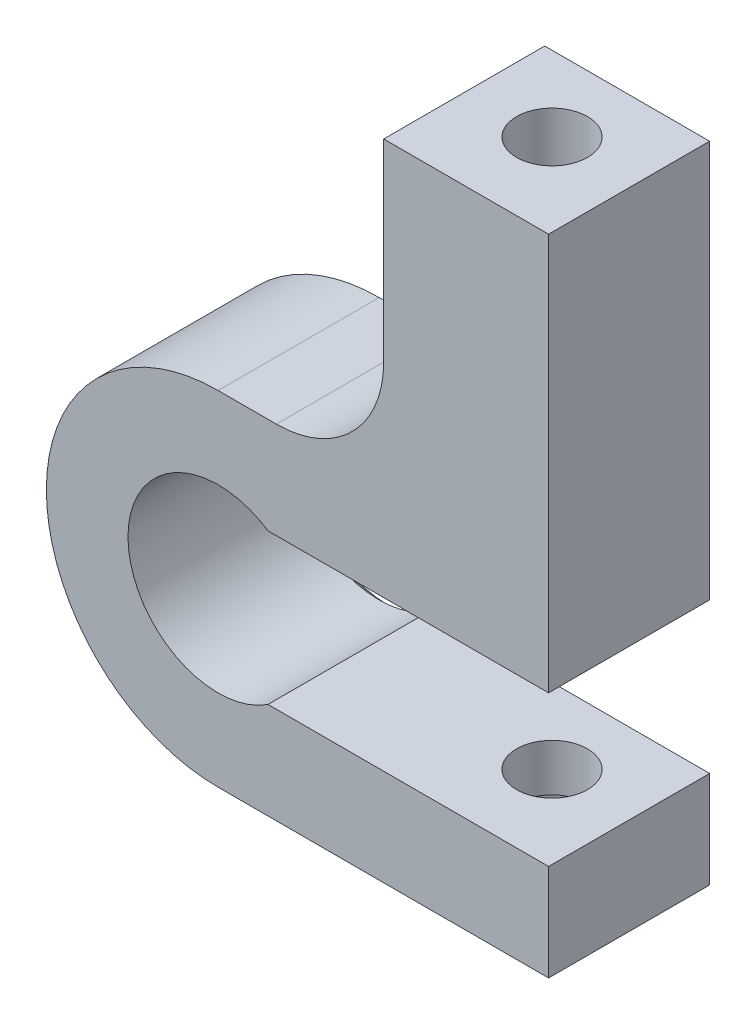
SolidWorks part; units mm, degrees
ref_plane "Front Plane" through (0, 0, 0) normal (0, 0, 1) x (1, 0, 0)
ref_plane "Top Plane" through (0, 0, 0) normal (0, 1, 0) x (1, 0, 0)
ref_plane "Right Plane" through (0, 0, 0) normal (1, 0, 0) x (0, 0, -1)
sketch "Sketch1" plane through (0, 0, 0) normal (0, 0, 1) x (1, 0, 0)
  line L0 (0, 8) -> (15.389, 8)
  line L1 (15.389, 8) -> (15.389, 3.5)
  line L2 (15.389, 3.5) -> (2.3216, 3.5)
  line L3 (-11.5353, 0) -> (18.1518, 0) construction
  line L4 (15.389, -3.5) -> (2.3216, -3.5)
  line L5 (15.389, -8) -> (15.389, -3.5)
  line L6 (0, -8) -> (15.389, -8)
  arc A0 (2.3216, 3.5) -> (2.3216, -3.5) centre (0, 0) ccw
  arc A2 (0, 8) -> (0, -8) centre (0, 0) ccw
  dimension "D1" = 4.2
  dimension "D2" = 8
  dimension "D3" = 15.389
  dimension "D4" = 7
extrude "Boss-Extrude1" add sketch "Sketch1" along normal blind 8
sketch "Sketch2" plane through (0, -8, 0) normal (0, -1, 0) x (1, 0, 0)
  line L1 (0, 8) -> (15.389, 8) construction
  line L3 (0, 8) -> (0, 0) construction
  circle A0 centre (11.549, 4) radius 1.65
  dimension "D1" = 4
  dimension "D2" = 3.3
  dimension "D3" = 11.549
extrude "Cut-Extrude1" cut sketch "Sketch2" against normal through all
sketch "Sketch3" plane through (0, -8, 0) normal (0, -1, 0) x (1, 0, 0)
  circle A0 centre (11.549, 4) radius 3
  dimension "D1" = 6
extrude "Cut-Extrude2" cut sketch "Sketch3" against normal blind 2.3
sketch "Sketch4" plane through (0, 3.5, 0) normal (0, -1, 0) x (1, 0, 0)
  line L0 (15.389, 8) -> (15.389, 0) construction
  line L8 (7.709, 0) -> (15.389, 0)
  line L9 (15.389, 0) -> (15.389, 8)
  line L10 (15.389, 8) -> (7.709, 8)
  line L11 (7.709, 8) -> (7.709, 0)
  circle A1 centre (11.549, 4) radius 1.65
  circle A2 centre (11.549, 4) radius 1.65
  dimension "D2" = 7.68
  dimension "D1" = 0
extrude "Boss-Extrude2" add sketch "Sketch4" against normal blind 18.5
fillet "Fillet1" radius 5 1 edges at (7.709, 8, 4)
chamfer "Chamfer1" distance 0.5 angle 45 11 edges at (7.6945, -8, 0) (-8, 0, 0) (1.3545, 8, 0) (6.2445, 9.4645, 0) (7.709, 17.5, 0) (11.549, 22, 0) (15.389, 12.75, 0) (8.8553, 3.5, 0) (-4.2, 0, 0) (8.8553, -3.5, 0) (15.389, -5.75, 0)
